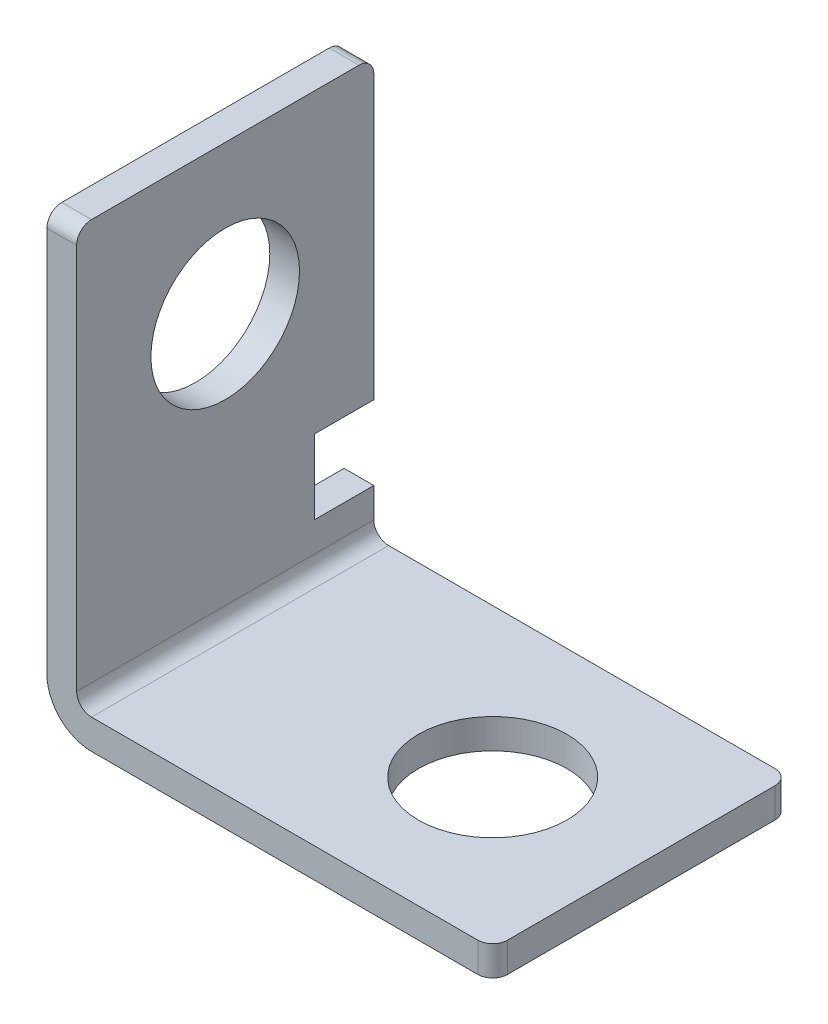
SolidWorks part; units mm, degrees
material "6061 Alloy"
ref_plane "Front Plane" through (0, 0, 0) normal (0, 0, 1) x (1, 0, 0)
ref_plane "Top Plane" through (0, 0, 0) normal (0, 1, 0) x (1, 0, 0)
ref_plane "Right Plane" through (0, 0, 0) normal (1, 0, 0) x (0, 0, -1)
sketch "Sketch1" plane through (0, 0, 0) normal (0, 0, 1) x (1, 0, 0)
  line L0 (0, 0) -> (-30, 0)
  line L1 (-30, 0) -> (-30, 30)
  line L2 (-30, 30) -> (-28, 30)
  line L3 (-28, 30) -> (-28, 2)
  line L4 (-28, 2) -> (0, 2)
  line L5 (0, 2) -> (0, 0)
  dimension "D1" = 30
  dimension "D2" = 2
  dimension "D3" = 2
  dimension "D4" = 30
extrude "Boss-Extrude1" add sketch "Sketch1" against normal blind 20
sketch "Sketch2" plane through (0, 2, 0) normal (0, 1, 0) x (1, 0, 0)
  line L0 (0, 20) -> (0, 0) construction
  line L1 (0, 0) -> (-28, 0) construction
  circle A0 centre (-10, 10) radius 5
  dimension "D1" = 10
  dimension "D2" = 10
  dimension "D3" = 10
extrude "Cut-Extrude1" cut sketch "Sketch2" against normal blind 20
sketch "Sketch3" plane through (-28, 0, 0) normal (1, 0, 0) x (0, 0, -1)
  line L0 (20, 30) -> (0, 30) construction
  line L1 (20, 2) -> (20, 30) construction
  line L3 (20, 5) -> (16, 5)
  line L4 (20, 5) -> (20, 10)
  line L5 (20, 10) -> (16, 10)
  line L6 (16, 5) -> (16, 10)
  circle A0 centre (10, 20) radius 5
  dimension "D3" = 10
  dimension "D1" = 10
  dimension "D2" = 10
  dimension "D4" = 20
  dimension "D5" = 5
  dimension "D6" = 4
extrude "Cut-Extrude2" cut sketch "Sketch3" against normal blind 20
fillet "Fillet1" radius 1 5 edges at (-29, 30, 0) (-29, 30, -20) (0, 1, 0) (0, 1, -20) (-28, 2, -10)
fillet "Fillet2" radius 3 1 edges at (-30, 0, -10)
